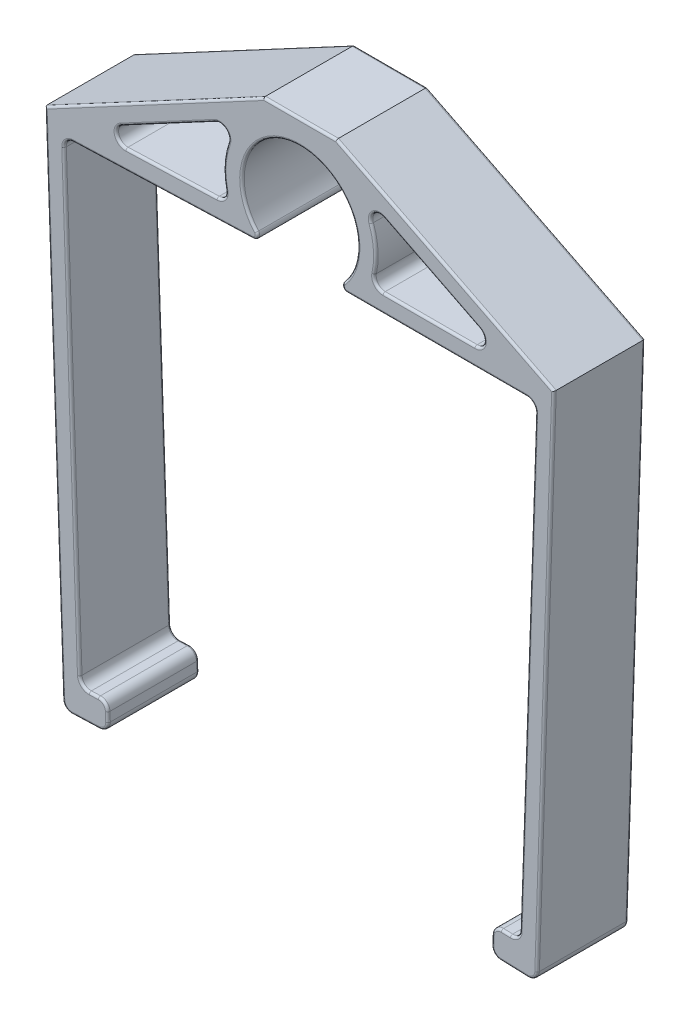
SolidWorks part; units mm, degrees
ref_plane "Front Plane" through (0, 0, 0) normal (0, 0, 1) x (1, 0, 0)
ref_plane "Top Plane" through (0, 0, 0) normal (0, 1, 0) x (1, 0, 0)
ref_plane "Right Plane" through (0, 0, 0) normal (1, 0, 0) x (0, 0, -1)
sketch "Sketch1" plane through (0, 0, 0) normal (0, 0, 1) x (1, 0, 0)
  line L0 (0, 6.9998) -> (0, -6.4819) construction
  line L1 (-6.0674, 0) -> (9.6842, 0) construction
  line L2 (1.9572, -2.5) -> (12.95, -2.5)
  line L4 (2, 4.5) -> (0, 4.5)
  line L5 (0, 4.5) -> (0, 4.175)
  line L9 (-12.9567, -2.8731) -> (-12.0598, -28.5574)
  line L11 (-12.0598, -28.5574) -> (-10.5607, -28.5051)
  line L16 (-2, 4.5) -> (0, 4.5)
  line L17 (-1.9706, -2.4895) -> (-12.9567, -2.8731)
  line L23 (2, 4.5) -> (13.95, -1.5)
  line L24 (3.8962, -1.5) -> (11.7214, -1.5)
  line L25 (11.7214, -1.5) -> (3.045, 2.8564)
  line L26 (-10.5607, -28.5051) -> (-10.5084, -30.0042)
  line L27 (-10.5084, -30.0042) -> (-13.0068, -30.0914)
  line L28 (-13.0068, -30.0914) -> (-13.991, -1.9086)
  line L29 (-13.991, -1.9086) -> (-2, 4.5)
  line L30 (-3.8962, -1.5) -> (-11.7064, -1.7727)
  line L31 (-11.7064, -1.7727) -> (-3.045, 2.8564)
  line L32 (0, 9.9007) -> (0, -33.7442) construction
  line L33 (12.95, -2.5) -> (12.0598, -28.5574)
  line L34 (10.5084, -30.0042) -> (13.0068, -30.0914)
  line L35 (10.5607, -28.5051) -> (10.5084, -30.0042)
  line L36 (12.0598, -28.5574) -> (10.5607, -28.5051)
  line L37 (13.0068, -30.0914) -> (13.95, -1.5)
  arc A0 (1.9572, -2.5) -> (-1.9706, -2.4895) centre (0, 0) ccw
  arc A1 (-3.045, 2.8564) -> (-3.8962, -1.5) centre (0, 0) ccw
  arc A2 (3.8962, -1.5) -> (3.045, 2.8564) centre (0, 0) ccw
  point P3 (0, -2.5)
  point P10 (0, -1.5)
  point P14 (7.3386, -1.5)
  point P15 (1.6243, 3.5)
  dimension "D1" = 6.35
  dimension "D2" = 8.35
  dimension "D3" = 10.9928
  dimension "D5" = 2
  dimension "D6" = 2.5
  dimension "D7" = 4.5
  dimension "D8" = 178
  dimension "D9" = 90
  dimension "D4" = 25.7
  dimension "D11" = 1.5
  dimension "D14" = 1
  dimension "D15" = 1
  dimension "D16" = 1.5
  dimension "D17" = 2.5
  dimension "D18" = 1
  dimension "D19" = 1
extrude "Boss-Extrude1" add sketch "Sketch1" along normal blind 5
fillet "Fillet1" radius 0.5 16 edges at (-13.0068, -30.0914, 2.5) (-10.5084, -30.0042, 2.5) (-10.5607, -28.5051, 2.5) (-12.0598, -28.5574, 2.5) (-12.9567, -2.8731, 2.5) (-3.045, 2.8564, 2.5) (-3.8962, -1.5, 2.5) (-11.7064, -1.7727, 2.5) (11.7214, -1.5, 2.5) (3.045, 2.8564, 2.5) (3.8962, -1.5, 2.5) (12.0598, -28.5574, 2.5) (13.0068, -30.0914, 2.5) (10.5084, -30.0042, 2.5) (10.5607, -28.5051, 2.5) (12.95, -2.5, 2.5)
fillet "Fillet2" radius 0.25 2 edges at (1.9572, -2.5, 2.5) (-1.9706, -2.4895, 2.5)
fillet "Fillet3" radius 0.125 80 edges at (10.0978, -1.1153, 5) (7.2218, 0.7592, 5) (4.0501, 1.9973, 5) (4.1649, 0.2907, 5) (4.1773, -1.3135, 5) (7.089, -1.5, 5) (-4.166, -1.3286, 5) (-4.1675, 0.2504, 5) (-4.0804, 1.9409, 5) (-7.2238, 0.623, 5) (-10.0527, -1.3277, 5) (-7.0484, -1.6101, 5) (-2.3437, -2.3594, 5) (-7.5108, -2.6829, 5) (-12.8052, -3.0143, 5) (-12.5082, -15.7153, 5) (-11.9185, -28.406, 5) (-11.3102, -28.5313, 5) (-10.7019, -28.6566, 5) (-10.5345, -29.2546, 5) (-10.6598, -29.8629, 5) (-11.7576, -30.0478, 5) (-12.8656, -29.94, 5) (-13.5076, -15.7502, 5) (-7.9955, 1.2957, 5) (0, 4.5, 5) (7.975, 1.5, 5) (13.4867, -15.5454, 5) (12.865, -29.9396, 5) (11.7571, -30.0478, 5) (10.6598, -29.8629, 5) (10.5345, -29.2546, 5) (10.7019, -28.6566, 5) (11.3101, -28.5313, 5) (11.9183, -28.4058, 5) (12.5046, -15.5372, 5) (12.7922, -2.6525, 5) (7.5074, -2.5, 5) (2.3547, -2.3535, 5) (-0.0064, 3.175, 5) (4.0501, 1.9973, 0) (7.2218, 0.7592, 0) (10.0978, -1.1153, 0) (7.089, -1.5, 0) (4.1773, -1.3135, 0) (4.1649, 0.2907, 0) (-4.0804, 1.9409, 0) (-4.1675, 0.2504, 0) (-4.166, -1.3286, 0) (-7.0484, -1.6101, 0) (-10.0527, -1.3277, 0) (-7.2238, 0.623, 0) (12.7922, -2.6525, 0) (12.5046, -15.5372, 0) (11.9183, -28.4058, 0) (11.3101, -28.5313, 0) (10.7019, -28.6566, 0) (10.5345, -29.2546, 0) (10.6598, -29.8629, 0) (11.7571, -30.0478, 0) (12.865, -29.9396, 0) (13.4867, -15.5454, 0) (7.975, 1.5, 0) (0, 4.5, 0) (-7.9955, 1.2957, 0) (-13.5076, -15.7502, 0) (-12.8656, -29.94, 0) (-11.7576, -30.0478, 0) (-10.6598, -29.8629, 0) (-10.5345, -29.2546, 0) (-10.7019, -28.6566, 0) (-11.3102, -28.5313, 0) (-11.9185, -28.406, 0) (-12.5082, -15.7153, 0) (-12.8052, -3.0143, 0) (-7.5108, -2.6829, 0) (-2.3437, -2.3594, 0) (-0.0064, 3.175, 0) (2.3547, -2.3535, 0) (7.5074, -2.5, 0)
